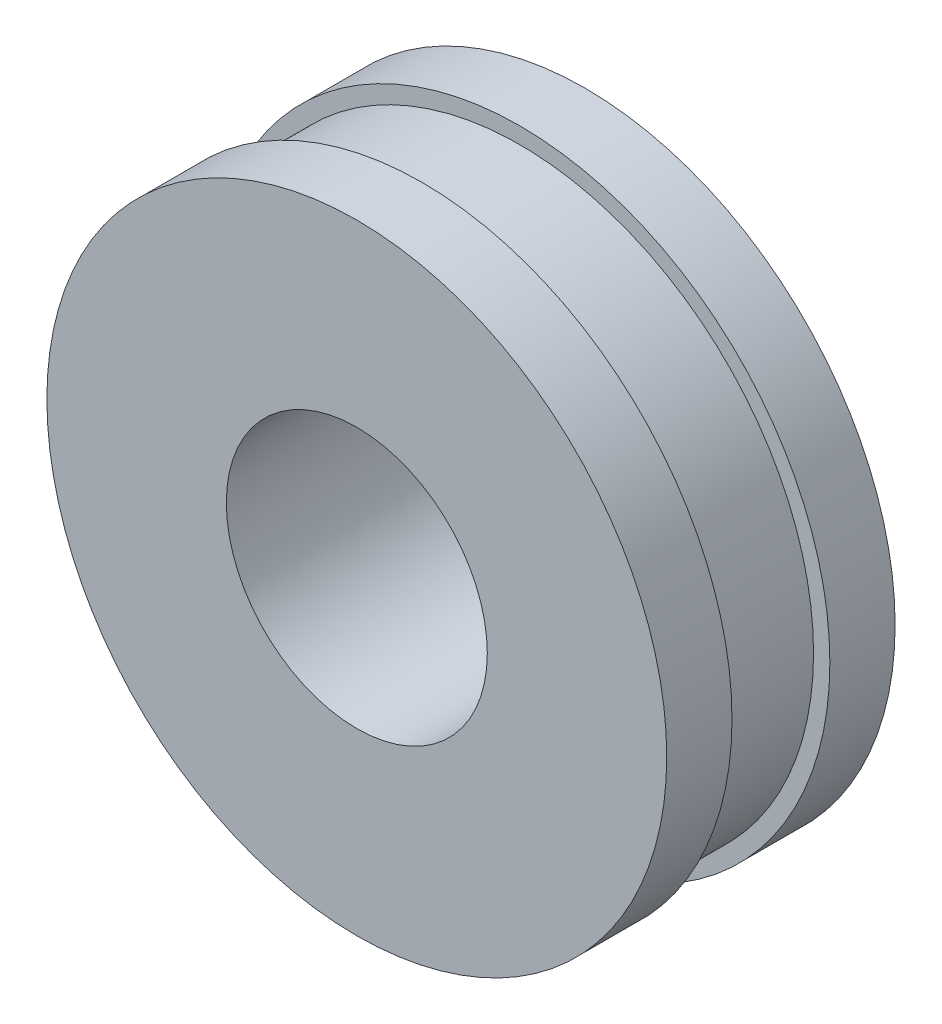
SolidWorks part; units mm, degrees
ref_plane "Front Plane" through (0, 0, 0) normal (0, 0, 1) x (1, 0, 0)
ref_plane "Top Plane" through (0, 0, 0) normal (0, 1, 0) x (1, 0, 0)
ref_plane "Right Plane" through (0, 0, 0) normal (1, 0, 0) x (0, 0, -1)
sketch "Sketch1" plane through (0, 0, 0) normal (0, 0, 1) x (1, 0, 0)
  circle A0 centre (0, 0) radius 7.1438
  circle A1 centre (0, 0) radius 3.175
  dimension "D1" = 14.2875
  dimension "D2" = 6.35
extrude "Boss-Extrude1" add sketch "Sketch1" along normal blind 2.3813
sketch "Sketch2" plane through (0, 0, 0) normal (0, 0, -1) x (-1, 0, 0)
  circle A0 centre (0, 0) radius 7.5406
  circle A1 centre (0, 0) radius 3.175
  dimension "D1" = 15.0812
extrude "Boss-Extrude2" add sketch "Sketch2" along normal blind 1.5875
sketch "Sketch3" plane through (0, 0, 2.3813) normal (0, 0, 1) x (1, 0, 0)
  circle A0 centre (0, 0) radius 3.175
  circle A1 centre (0, 0) radius 7.5406
  dimension "D1" = 15.0812
extrude "Boss-Extrude3" add sketch "Sketch3" along normal blind 1.5875
